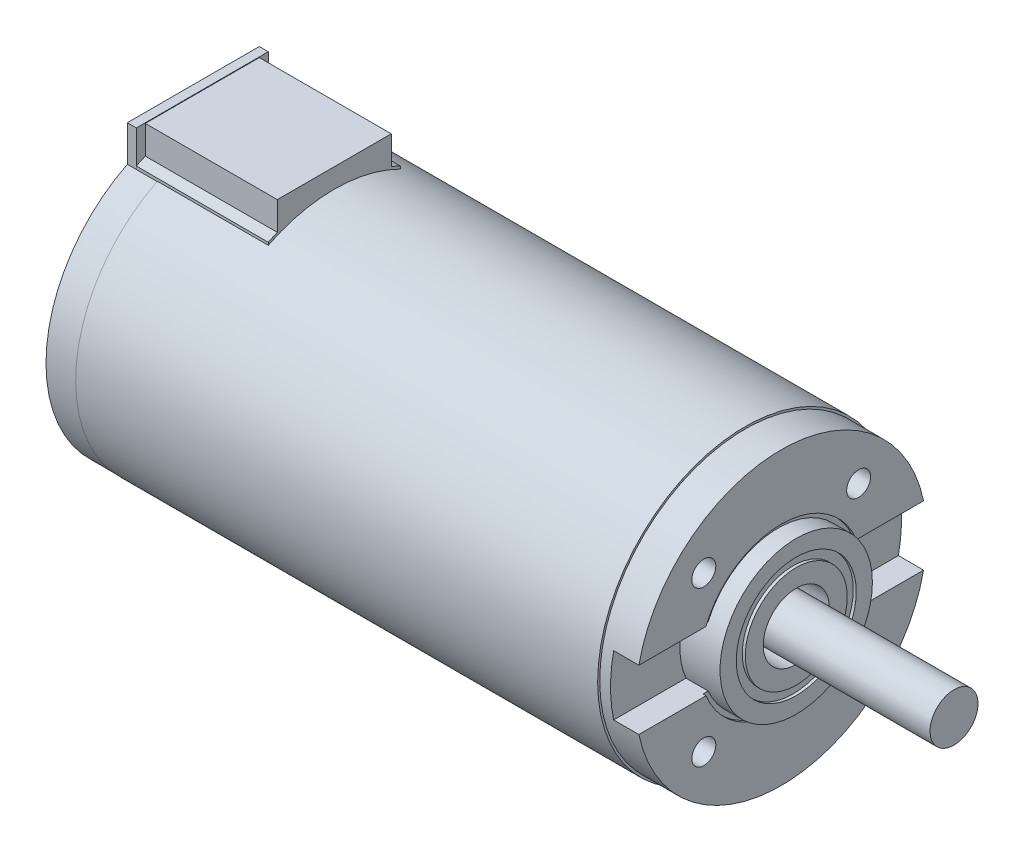
SolidWorks part; units mm, degrees
ref_plane "Front Plane" through (0, 0, 0) normal (0, 0, 1) x (1, 0, 0)
ref_plane "Top Plane" through (0, 0, 0) normal (0, 1, 0) x (1, 0, 0)
ref_plane "Right Plane" through (0, 0, 0) normal (1, 0, 0) x (0, 0, -1)
sketch "Sketch1" plane through (0, 0, 0) normal (1, 0, 0) x (0, 0, -1)
  circle A0 centre (0, 0) radius 24.6
  dimension "D1" = 49.2
extrude "Boss-Extrude1" add sketch "Sketch1" against normal blind 87
sketch "Sketch2" plane through (0, 0, 0) normal (1, 0, 0) x (0, 0, -1)
  circle A0 centre (0, 0) radius 24.25
  dimension "D1" = 48.5
extrude "Boss-Extrude2" add sketch "Sketch2" along normal blind 6
sketch "Sketch3" plane through (-87, 0, 0) normal (-1, 0, 0) x (0, 0, 1)
  line L0 (0, 0) -> (0, 40.0851) construction
  line L1 (11, 27.9477) -> (-11, 27.9477)
  line L2 (-11, 27.9477) -> (-11, 21.9477)
  line L3 (11, 27.9477) -> (11, 21.9477)
  arc A0 (-11, 21.9477) -> (11, 21.9477) centre (0, 0) ccw
  point P8 (0, 27.9477)
  dimension "D1" = 49.1
  dimension "D2" = 11
  dimension "D3" = 6
extrude "Boss-Extrude3" add sketch "Sketch3" along normal blind 5
sketch "Sketch4" plane through (6, 0, 0) normal (1, 0, 0) x (0, 0, -1)
  line L0 (-24.6, 0) -> (24.6, 0) construction
  line L1 (-23.7289, 5) -> (-11.6743, 5)
  line L2 (-23.7289, -5) -> (-11.6743, -5)
  line L3 (11.6743, -5) -> (23.7289, -5)
  line L4 (11.6743, 5) -> (23.7289, 5)
  line L5 (-12.9047, 12.9047) -> (0, 0) construction
  arc A0 (-11.6743, 5) -> (-11.6743, -5) centre (0, 0) ccw
  circle A1 centre (0, 0) radius 24.6 construction
  circle A2 centre (0, 0) radius 24.25 construction
  arc A3 (-23.7289, 5) -> (-23.7289, -5) centre (0, 0) ccw
  arc A4 (23.7289, -5) -> (23.7289, 5) centre (0, 0) ccw
  arc A5 (11.6743, -5) -> (11.6743, 5) centre (0, 0) ccw
  circle A6 centre (0, 0) radius 5.5
  circle A8 centre (-12.9047, 12.9047) radius 2
  circle A9 centre (12.9047, 12.9047) radius 2
  circle A10 centre (12.9047, -12.9047) radius 2
  circle A11 centre (-12.9047, -12.9047) radius 2
  point P28 (0, 0)
  dimension "D1" = 25.4
  dimension "D3" = 11
  dimension "D5" = 4
  dimension "D2" = 5
  dimension "D4" = 5
  dimension "D6" = 45
  dimension "D7" = 18.25
  dimension "D8" = 4
extrude "Cut-Extrude1" cut sketch "Sketch4" against normal blind 4.2
sketch "Sketch5" plane through (6, 0, 0) normal (1, 0, 0) x (0, 0, -1)
  line L0 (-11.6743, 5) -> (-12.5399, 5)
  line L1 (-11.6743, 5) -> (-23.7289, 5) construction
  line L2 (-11.6743, -5) -> (-12.5399, -5)
  line L3 (-23.7289, -5) -> (-11.6743, -5) construction
  line L4 (11.6743, -5) -> (12.5399, -5)
  line L5 (11.6743, -5) -> (23.7289, -5) construction
  line L6 (11.6743, 5) -> (12.5399, 5)
  line L7 (23.7289, 5) -> (11.6743, 5) construction
  arc A0 (11.6743, 5) -> (-11.6743, 5) centre (0, 0) ccw
  arc A1 (12.5399, 5) -> (-12.5399, 5) centre (0, 0) ccw
  arc A2 (-12.5399, -5) -> (12.5399, -5) centre (0, 0) ccw
  arc A3 (-11.6743, -5) -> (11.6743, -5) centre (0, 0) ccw
  dimension "D1" = 27
extrude "Cut-Extrude2" cut sketch "Sketch5" against normal blind 0.5
sketch "Sketch6" plane through (6, 0, 0) normal (1, 0, 0) x (0, 0, -1)
  circle A0 centre (0, 0) radius 12.7
  circle A1 centre (0, 0) radius 5.5
extrude "Boss-Extrude4" add sketch "Sketch6" along normal blind 2.5
sketch "Sketch7" plane through (8.5, 0, 0) normal (1, 0, 0) x (0, 0, -1)
  circle A0 centre (0, 0) radius 10
  circle A1 centre (0, 0) radius 8.5
  dimension "D1" = 20
  dimension "D2" = 17
extrude "Cut-Extrude3" cut sketch "Sketch7" against normal blind 0.5
sketch "Sketch8" plane through (1.8, 0, 0) normal (1, 0, 0) x (0, 0, -1)
  circle A0 centre (0, 0) radius 4
  dimension "D1" = 8
extrude "Boss-Extrude5" add sketch "Sketch8" along normal blind 33
sketch "Sketch9" plane through (-87, 0, 0) normal (1, 0, 0) x (0, 0, -1)
  line L6 (11, 21.9477) -> (11, 27.9477)
  line L7 (11, 27.9477) -> (-11, 27.9477)
  line L8 (-11, 27.9477) -> (-11, 21.9477)
  arc A4 (11, 21.9477) -> (-11, 21.9477) centre (0, 0) ccw
extrude "Cut-Extrude4" cut sketch "Sketch9" against normal blind 3.5
sketch "Sketch11" plane through (-90.5, 0, 0) normal (1, 0, 0) x (0, 0, -1)
  line L0 (0, 0) -> (0, 27.9477) construction
  line L1 (11, 27.9477) -> (-11, 27.9477) construction
  line L3 (-9.5, 27.8477) -> (-9.5, 23.1247)
  line L4 (-11.0025, 22.4487) -> (-11, 21.9477)
  line L5 (-11, 27.9477) -> (-11, 21.9477) construction
  line L6 (9.5, 27.8477) -> (9.5, 23.1247)
  line L7 (11.0025, 22.4487) -> (11, 21.9477)
  line L8 (-9.5, 27.8477) -> (9.5, 27.8477)
  arc A0 (-9.5, 23.1247) -> (-11.0025, 22.4487) centre (0, 0) ccw
  arc A1 (11, 21.9477) -> (-11, 21.9477) centre (0, 0) ccw construction
  arc A2 (11, 21.9477) -> (-11, 21.9477) centre (0, 0) ccw
  arc A3 (9.5, 23.1247) -> (11.0025, 22.4487) centre (0, 0) cw
  dimension "D1" = 50
  dimension "D2" = 1.5
  dimension "D3" = 0.1
extrude "Boss-Extrude7" add sketch "Sketch11" along normal blind 22
sketch "Sketch12" plane through (0, 0, 0) normal (0, 0, 1) x (1, 0, 0)
  line L0 (0, 0) -> (-127.6331, 0) construction
  line L1 (-92, 4) -> (-97, 4)
  line L2 (-92, 21.9477) -> (-92, -24.55) construction
  line L3 (-97, 4) -> (-97, 2.5)
  line L4 (-97, 2.5) -> (-107, 2.5)
  line L5 (-107, 2.5) -> (-107, 0)
  line L6 (-107, 0) -> (-92, 0)
  line L7 (-92, 0) -> (-92, 4)
  dimension "D1" = 15
  dimension "D2" = 4
  dimension "D3" = 2.5
  dimension "D4" = 10
revolve "Revolve1" add sketch "Sketch12" angle 360 about L0
